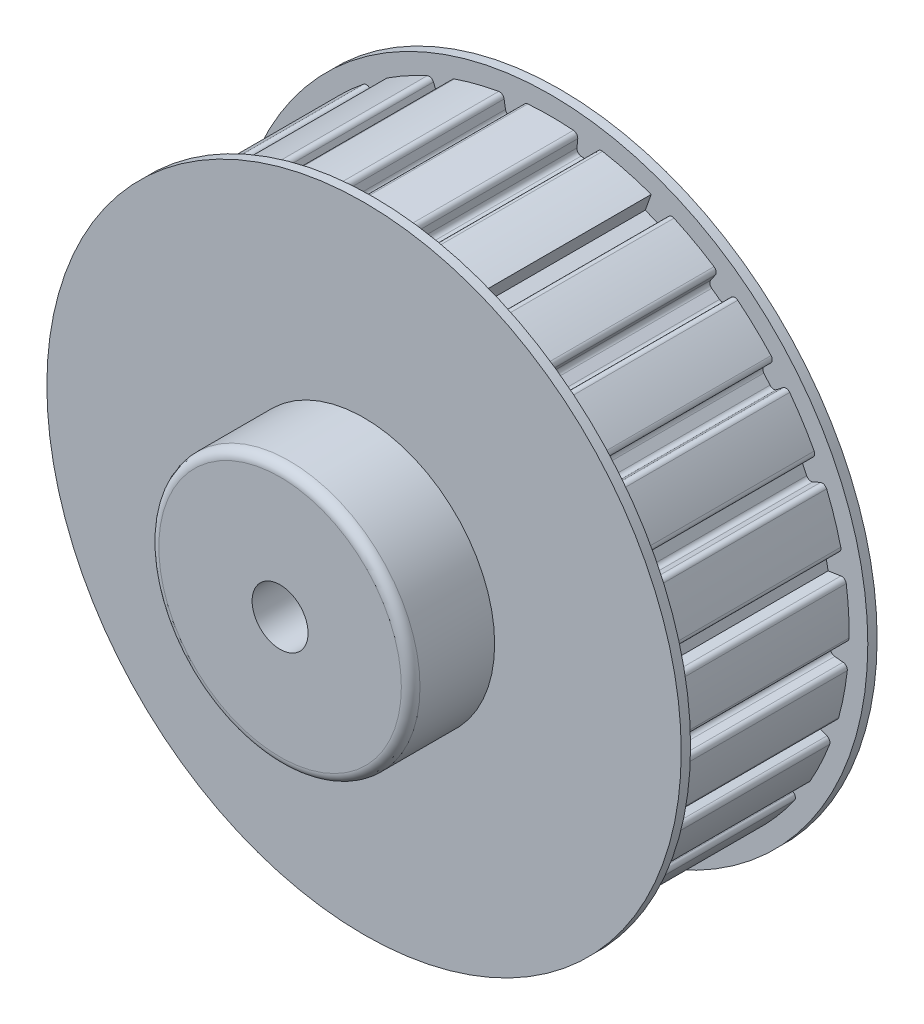
SolidWorks part; units mm, degrees
ref_plane "Front Plane" through (0, 0, 0) normal (0, 0, 1) x (1, 0, 0)
ref_plane "Top Plane" through (0, 0, 0) normal (0, 1, 0) x (1, 0, 0)
ref_plane "Right Plane" through (0, 0, 0) normal (1, 0, 0) x (0, 0, -1)
ref_plane "Plane1" through (0, 0, 0) normal (1, 0, 0) x (0, 0, -1)
ref_plane "Plane2" through (0, 0, 0) normal (0, 1, 0) x (1, 0, 0)
ref_plane "Plane3" through (0, 0, 0) normal (0, 0, 1) x (1, 0, 0)
sketch "Sketch1" plane through (0, 0, 0) normal (0, 0, 1) x (1, 0, 0)
  circle A0 centre (0, 0) radius 34
  dimension "D1" = 68
extrude "Boss-Extrude1" add sketch "Sketch1" along normal blind 1 contours A0
sketch "Sketch4" plane through (0, 0, 0) normal (0, 0, 1) x (1, 0, 0)
  circle A0 centre (0, 0) radius 32
  dimension "D1" = 64
extrude "Boss-Extrude2" add sketch "Sketch4" against normal blind 19
ref_plane "Plane4" through (0, 0, -19) normal (0, 0, 1) x (1, 0, 0)
sketch "Sketch8" plane through (0, 0, -19) normal (0, 0, 1) x (1, 0, 0)
  line L0 (-1, -30.0899) -> (-1.0665, -32.0899)
  line L1 (1, -30.0899) -> (-1, -30.0899)
  line L2 (1, -30.0899) -> (1.0665, -32.0899)
  line L3 (0, -36.4144) -> (0, -25.1458) construction
  line L4 (0, -35.6864) -> (0, 35.6864) construction
  line L5 (6.5145, -29.3932) -> (6.9475, -31.3469)
  line L6 (8.4516, -28.8958) -> (9.0134, -30.8165)
  line L7 (8.4516, -28.8958) -> (6.5145, -29.3932)
  line L8 (13.6196, -26.8497) -> (14.5249, -28.6343)
  line L9 (15.3722, -25.8862) -> (16.394, -27.6068)
  line L10 (15.3722, -25.8862) -> (13.6196, -26.8497)
  line L11 (19.869, -22.6191) -> (21.1896, -24.1225)
  line L12 (21.3269, -21.25) -> (22.7444, -22.6624)
  line L13 (21.3269, -21.25) -> (19.869, -22.6191)
  line L14 (24.8699, -16.9673) -> (26.5229, -18.0951)
  line L15 (25.9415, -15.2786) -> (27.6658, -16.2942)
  line L16 (25.9415, -15.2786) -> (24.8699, -16.9673)
  line L17 (28.3081, -10.2493) -> (30.1897, -10.9306)
  line L18 (28.9262, -8.3472) -> (30.8488, -8.902)
  line L19 (28.9262, -8.3472) -> (28.3081, -10.2493)
  line L20 (29.9677, -2.8874) -> (31.9596, -3.0793)
  line L21 (30.0933, -0.8913) -> (32.0935, -0.9506)
  line L22 (30.0933, -0.8913) -> (29.9677, -2.8874)
  line L23 (29.7443, 4.656) -> (31.7213, 4.9655)
  line L24 (29.3695, 6.6206) -> (31.3216, 7.0606)
  line L25 (29.3695, 6.6206) -> (29.7443, 4.656)
  line L26 (27.6519, 11.9068) -> (29.4898, 12.6982)
  line L27 (26.8003, 13.7165) -> (28.5817, 14.6282)
  line L28 (26.8003, 13.7165) -> (27.6519, 11.9068)
  line L29 (23.8221, 18.4095) -> (25.4054, 19.6331)
  line L30 (22.5472, 19.9505) -> (24.0459, 21.2766)
  line L31 (22.5472, 19.9505) -> (23.8221, 18.4095)
  line L32 (18.4954, 23.7554) -> (19.7247, 25.3344)
  line L33 (16.8774, 24.931) -> (17.9992, 26.5881)
  line L34 (16.8774, 24.931) -> (18.4954, 23.7554)
  line L35 (12.0066, 27.6087) -> (12.8046, 29.4438)
  line L36 (10.147, 28.345) -> (10.8215, 30.229)
  line L37 (10.147, 28.345) -> (12.0066, 27.6087)
  line L38 (4.7634, 29.7273) -> (5.08, 31.7032)
  line L39 (2.7791, 29.9779) -> (2.9639, 31.9705)
  line L40 (2.7791, 29.9779) -> (4.7634, 29.7273)
  line L41 (-2.7791, 29.9779) -> (-2.9639, 31.9705)
  line L42 (-4.7634, 29.7273) -> (-5.08, 31.7032)
  line L43 (-4.7634, 29.7273) -> (-2.7791, 29.9779)
  line L44 (-10.147, 28.345) -> (-10.8215, 30.229)
  line L45 (-12.0066, 27.6087) -> (-12.8046, 29.4438)
  line L46 (-12.0066, 27.6087) -> (-10.147, 28.345)
  line L47 (-16.8774, 24.931) -> (-17.9992, 26.5881)
  line L48 (-18.4954, 23.7554) -> (-19.7247, 25.3344)
  line L49 (-18.4954, 23.7554) -> (-16.8774, 24.931)
  line L50 (-22.5472, 19.9505) -> (-24.0459, 21.2766)
  line L51 (-23.8221, 18.4095) -> (-25.4054, 19.6331)
  line L52 (-23.8221, 18.4095) -> (-22.5472, 19.9505)
  line L53 (-26.8003, 13.7165) -> (-28.5817, 14.6282)
  line L54 (-27.6519, 11.9068) -> (-29.4898, 12.6982)
  line L55 (-27.6519, 11.9068) -> (-26.8003, 13.7165)
  line L56 (-29.3695, 6.6206) -> (-31.3216, 7.0606)
  line L57 (-29.7443, 4.656) -> (-31.7213, 4.9655)
  line L58 (-29.7443, 4.656) -> (-29.3695, 6.6206)
  line L59 (-30.0933, -0.8913) -> (-32.0935, -0.9506)
  line L60 (-29.9677, -2.8874) -> (-31.9596, -3.0793)
  line L61 (-29.9677, -2.8874) -> (-30.0933, -0.8913)
  line L62 (-28.9262, -8.3472) -> (-30.8488, -8.902)
  line L63 (-28.3081, -10.2493) -> (-30.1897, -10.9306)
  line L64 (-28.3081, -10.2493) -> (-28.9262, -8.3472)
  line L65 (-25.9415, -15.2786) -> (-27.6658, -16.2942)
  line L66 (-24.8699, -16.9673) -> (-26.5229, -18.0951)
  line L67 (-24.8699, -16.9673) -> (-25.9415, -15.2786)
  line L68 (-21.3269, -21.25) -> (-22.7444, -22.6624)
  line L69 (-19.869, -22.6191) -> (-21.1896, -24.1225)
  line L70 (-19.869, -22.6191) -> (-21.3269, -21.25)
  line L71 (-15.3722, -25.8862) -> (-16.394, -27.6068)
  line L72 (-13.6196, -26.8497) -> (-14.5249, -28.6343)
  line L73 (-13.6196, -26.8497) -> (-15.3722, -25.8862)
  line L74 (-8.4516, -28.8958) -> (-9.0134, -30.8165)
  line L75 (-6.5145, -29.3932) -> (-6.9475, -31.3469)
  line L76 (-6.5145, -29.3932) -> (-8.4516, -28.8958)
  arc A0 (-1.0665, -32.0899) -> (1.0665, -32.0899) centre (0, 0) ccw
  arc A1 (6.9475, -31.3469) -> (9.0134, -30.8165) centre (0, 0) ccw
  arc A2 (14.5249, -28.6343) -> (16.394, -27.6068) centre (0, 0) ccw
  arc A3 (21.1896, -24.1225) -> (22.7444, -22.6624) centre (0, 0) ccw
  arc A4 (26.5229, -18.0951) -> (27.6658, -16.2942) centre (0, 0) ccw
  arc A5 (30.1897, -10.9306) -> (30.8488, -8.902) centre (0, 0) ccw
  arc A6 (31.9596, -3.0793) -> (32.0935, -0.9506) centre (0, 0) ccw
  arc A7 (31.7213, 4.9655) -> (31.3216, 7.0606) centre (0, 0) ccw
  arc A8 (29.4898, 12.6982) -> (28.5817, 14.6282) centre (0, 0) ccw
  arc A9 (25.4054, 19.6331) -> (24.0459, 21.2766) centre (0, 0) ccw
  arc A10 (19.7247, 25.3344) -> (17.9992, 26.5881) centre (0, 0) ccw
  arc A11 (12.8046, 29.4438) -> (10.8215, 30.229) centre (0, 0) ccw
  arc A12 (5.08, 31.7032) -> (2.9639, 31.9705) centre (0, 0) ccw
  arc A13 (-2.9639, 31.9705) -> (-5.08, 31.7032) centre (0, 0) ccw
  arc A14 (-10.8215, 30.229) -> (-12.8046, 29.4438) centre (0, 0) ccw
  arc A15 (-17.9992, 26.5881) -> (-19.7247, 25.3344) centre (0, 0) ccw
  arc A16 (-24.0459, 21.2766) -> (-25.4054, 19.6331) centre (0, 0) ccw
  arc A17 (-28.5817, 14.6282) -> (-29.4898, 12.6982) centre (0, 0) ccw
  arc A18 (-31.3216, 7.0606) -> (-31.7213, 4.9655) centre (0, 0) ccw
  arc A19 (-32.0935, -0.9506) -> (-31.9596, -3.0793) centre (0, 0) ccw
  arc A20 (-30.8488, -8.902) -> (-30.1897, -10.9306) centre (0, 0) ccw
  arc A21 (-27.6658, -16.2942) -> (-26.5229, -18.0951) centre (0, 0) ccw
  arc A22 (-22.7444, -22.6624) -> (-21.1896, -24.1225) centre (0, 0) ccw
  arc A23 (-16.394, -27.6068) -> (-14.5249, -28.6343) centre (0, 0) ccw
  arc A24 (-9.0134, -30.8165) -> (-6.9475, -31.3469) centre (0, 0) ccw
  point P108 (0, 0)
  dimension "D1" = 2
  dimension "D2" = 2
  dimension "D3" = 25
extrude "Cut-Extrude1" cut sketch "Sketch8" along normal blind 19
sketch "Sketch9" plane through (0, 0, -19) normal (0, 0, 1) x (1, 0, 0)
  circle A0 centre (0, 0) radius 34
extrude "Boss-Extrude3" add sketch "Sketch9" against normal blind 1
sketch "Sketch10" plane through (0, 0, 0) normal (0, 0, 1) x (1, 0, 0)
  circle A0 centre (0, 0) radius 14
  dimension "D1" = 28
extrude "Boss-Extrude4" add sketch "Sketch10" along normal blind 10
sketch "Sketch11" plane through (0, 0, 0) normal (0, 0, 1) x (1, 0, 0)
  circle A0 centre (0, 0) radius 3
  dimension "D1" = 6
extrude "Cut-Extrude2" cut sketch "Sketch11" against normal through all both and the other way through all
fillet "Fillet1" radius 1 1 edges at (14, 0, 10)
fillet "Fillet2" radius 0.5 55 edges at (4.7634, 29.7273, -9.5) (2.7791, 29.9779, -9.5) (-4.7634, 29.7273, -9.5) (-12.7617, 29.3452, -9.5) (-12.0066, 27.6087, -9.5) (5.063, 31.5969, -9.5) (2.9539, 31.8634, -9.5) (-2.9539, 31.8634, -9.5) (-5.063, 31.5969, -9.5) (-10.7852, 30.1277, -9.5) (-10.147, 28.345, -9.5) (-17.9388, 26.499, -9.5) (-16.8774, 24.931, -9.5) (-18.4954, 23.7554, -9.5) (-19.6586, 25.2495, -9.5) (-22.5472, 19.9505, -9.5) (-23.8221, 18.4095, -9.5) (-29.391, 12.6557, -9.5) (-27.6519, 11.9068, -9.5) (-31.615, 4.9488, -9.5) (-29.7443, 4.656, -9.5) (-25.3203, 19.5673, -9.5) (-23.9653, 21.2053, -9.5) (-28.4859, 14.5792, -9.5) (-26.8003, 13.7165, -9.5) (-29.3695, 6.6206, -9.5) (-31.2167, 7.037, -9.5) (-31.986, -0.9474, -9.5) (-30.0933, -0.8913, -9.5) (-31.8525, -3.069, -9.5) (-29.9677, -2.8874, -9.5) (-30.7455, -8.8722, -9.5) (-28.9262, -8.3472, -9.5) (-30.0886, -10.894, -9.5) (-28.3081, -10.2493, -9.5) (-24.8699, -16.9673, -9.5) (-26.4341, -18.0344, -9.5) (-27.5731, -16.2396, -9.5) (-25.9415, -15.2786, -9.5) (-22.6682, -22.5865, -9.5) (-21.3269, -21.25, -9.5) (-21.1186, -24.0417, -9.5) (-19.869, -22.6191, -9.5) (-14.4762, -28.5384, -9.5) (-13.6196, -26.8497, -9.5) (-15.3722, -25.8862, -9.5) (-16.339, -27.5143, -9.5) (-8.4516, -28.8958, -9.5) (-8.9832, -30.7132, -9.5) (-6.9242, -31.2419, -9.5) (-6.5145, -29.3932, -9.5) (1.0629, -31.9823, -9.5) (1, -30.0899, -9.5) (-1, -30.0899, -9.5) (-1.0629, -31.9823, -9.5)
fillet "Fillet3" radius 0.5 38 edges at (6.9242, -31.2419, -9.5) (6.5145, -29.3932, -9.5) (8.9832, -30.7132, -9.5) (8.4516, -28.8958, -9.5) (16.339, -27.5143, -9.5) (15.3722, -25.8862, -9.5) (21.3269, -21.25, -9.5) (22.6682, -22.5865, -9.5) (21.1186, -24.0417, -9.5) (19.869, -22.6191, -9.5) (26.4341, -18.0344, -9.5) (24.8699, -16.9673, -9.5) (25.9415, -15.2786, -9.5) (27.5731, -16.2396, -9.5) (30.7455, -8.8722, -9.5) (28.9262, -8.3472, -9.5) (30.0886, -10.894, -9.5) (28.3081, -10.2493, -9.5) (31.986, -0.9474, -9.5) (30.0933, -0.8913, -9.5) (29.9677, -2.8874, -9.5) (31.8525, -3.069, -9.5) (31.615, 4.9488, -9.5) (31.2167, 7.037, -9.5) (29.391, 12.6557, -9.5) (27.6519, 11.9068, -9.5) (26.8003, 13.7165, -9.5) (28.4859, 14.5792, -9.5) (23.8221, 18.4095, -9.5) (25.3203, 19.5673, -9.5) (22.5472, 19.9505, -9.5) (23.9653, 21.2053, -9.5) (18.4954, 23.7554, -9.5) (19.6586, 25.2495, -9.5) (16.8774, 24.931, -9.5) (17.9388, 26.499, -9.5) (12.7617, 29.3452, -9.5) (12.0066, 27.6087, -9.5)
